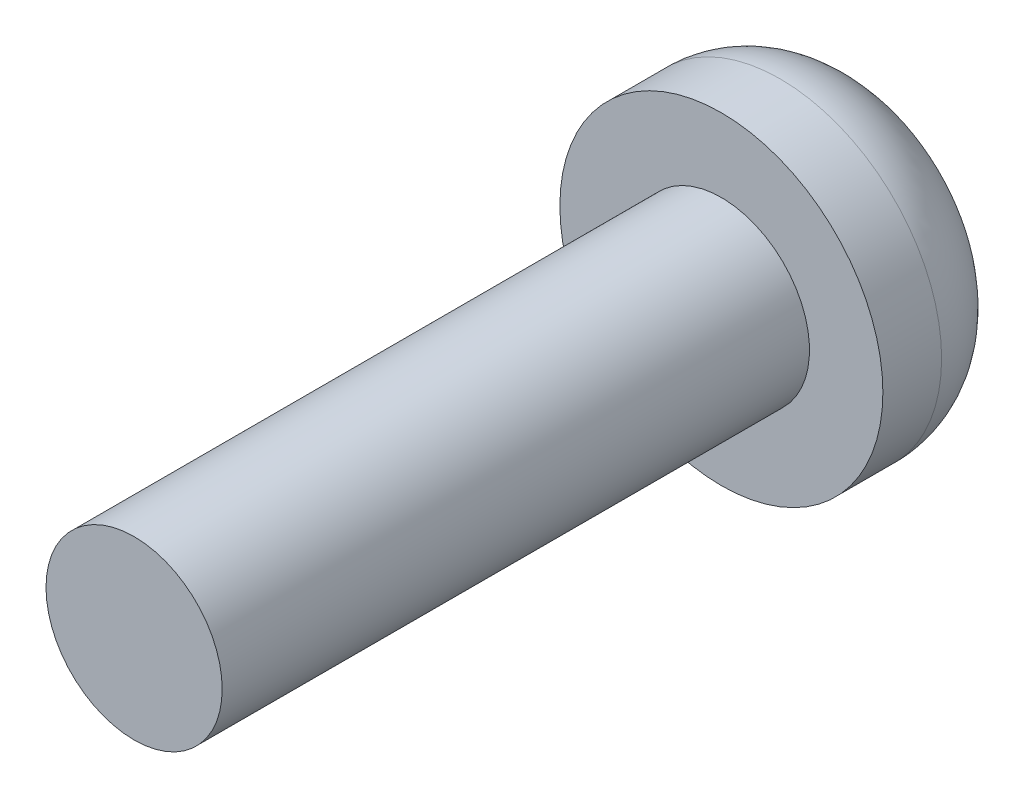
SolidWorks part; units mm, degrees
ref_plane "Front Plane" through (0, 0, 0) normal (0, 0, 1) x (1, 0, 0)
ref_plane "Top Plane" through (0, 0, 0) normal (0, 1, 0) x (1, 0, 0)
ref_plane "Right Plane" through (0, 0, 0) normal (1, 0, 0) x (0, 0, -1)
sketch "Sketch1" plane through (0, 0, 0) normal (0, 0, 1) x (1, 0, 0)
  circle A0 centre (0, 0) radius 1.5
  dimension "D1" = 3
extrude "Boss-Extrude1" add sketch "Sketch1" along normal blind 10
sketch "Sketch2" plane through (0, 0, 0) normal (0, 0, -1) x (-1, 0, 0)
  circle A0 centre (0, 0) radius 2.75
  dimension "D1" = 5.5
extrude "Boss-Extrude2" add sketch "Sketch2" along normal blind 2.5
fillet "Fillet1" radius 1.5 1 edges at (-2.75, 0, -2.5)
